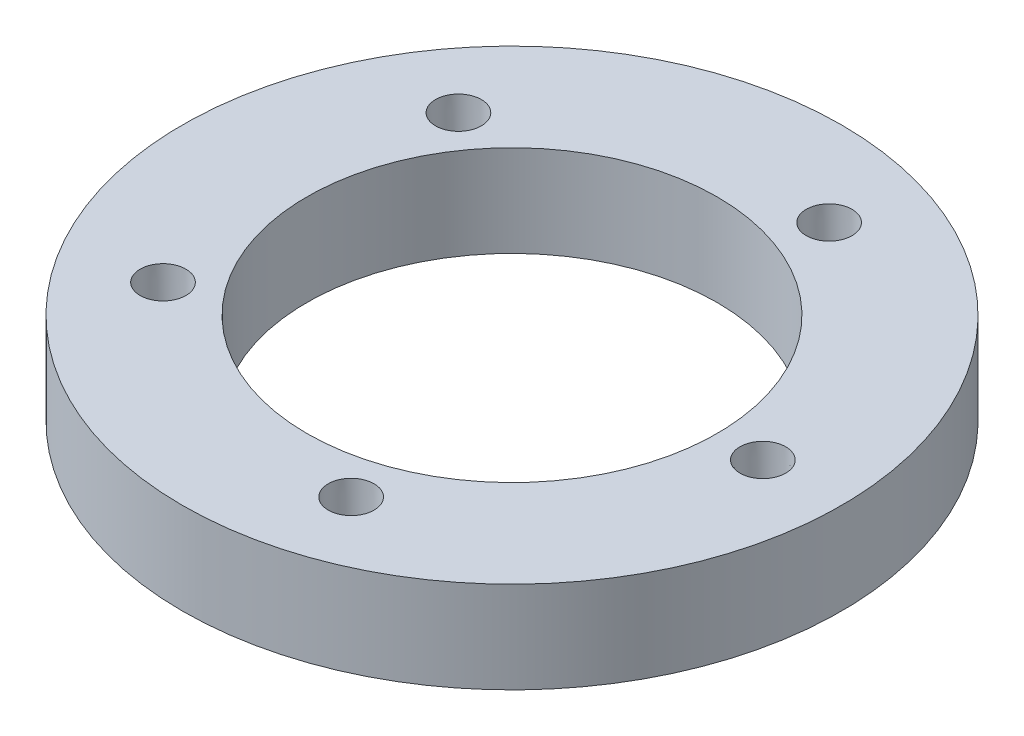
SolidWorks part; units mm, degrees
ref_plane "Front Plane" through (0, 0, 0) normal (0, 0, 1) x (1, 0, 0)
ref_plane "Top Plane" through (0, 0, 0) normal (0, 1, 0) x (1, 0, 0)
ref_plane "Right Plane" through (0, 0, 0) normal (1, 0, 0) x (0, 0, -1)
sketch "Sketch1" plane through (0, 0, 0) normal (0, 1, 0) x (1, 0, 0)
  circle A0 centre (0, 0) radius 11.2
  circle A1 centre (0, 0) radius 16.2
  dimension "D1" = 22.4
  dimension "D2" = 5
extrude "Boss-Extrude2" add sketch "Sketch1" along normal blind 5
sketch "Sketch2" plane through (0, 5, 0) normal (0, 1, 0) x (1, 0, 0)
  line L0 (-11.2, 0) -> (-16.2, 0) construction
  line L1 (-12.5, 0.9943) -> (-12.5, -1.1473) construction
  line L2 (0.0123, 0.0374) -> (12.4508, 0.046) construction
  circle A0 centre (0, 0) radius 11.2 construction
  circle A1 centre (0, 0) radius 16.2 construction
  arc A2 (-11.7329, 7.0732) -> (-11.8029, -6.9556) centre (0, 0) ccw
  circle A3 centre (13.7, 0) radius 1.25
  circle A4 centre (4.2064, -12.9919) radius 1.25
  circle A5 centre (-11.0833, -7.9777) radius 1.25
  circle A6 centre (-11.0393, 8.1132) radius 1.25
  circle A7 centre (4.2776, 13.0437) radius 1.25
  arc A8 (3.0664, 13.3524) -> (-10.2539, 9.0856) centre (0, 0) ccw
  arc A9 (13.643, 1.2487) -> (5.4365, 12.5752) centre (0, 0) ccw
  arc A10 (5.3915, -12.5945) -> (13.643, -1.2487) centre (0, 0) ccw
  arc A11 (-10.3425, -8.9846) -> (3.0132, -13.3645) centre (0, 0) ccw
  dimension "D1" = 2.5
  dimension "D3" = 2.5
  dimension "D2" = 5
extrude "Cut-Extrude1" cut sketch "Sketch2" against normal blind 5 draft 2 contours A6 | A5 | A4 | A3 | A7
sketch "Sketch3" plane through (0, 5, 0) normal (0, 1, 0) x (1, 0, 0)
  circle A0 centre (0, 0) radius 16
  circle A1 centre (0, 0) radius 18
  dimension "D1" = 2
extrude "Boss-Extrude4" add sketch "Sketch3" against normal up to surface (5 mm away) up to face at (4.2776, 0, -11.9683)
equation "\"outer-diameter\"= 20"
equation "\"screw-diameter\"= 2"
equation "\"bearing-thickness\"= 5"
